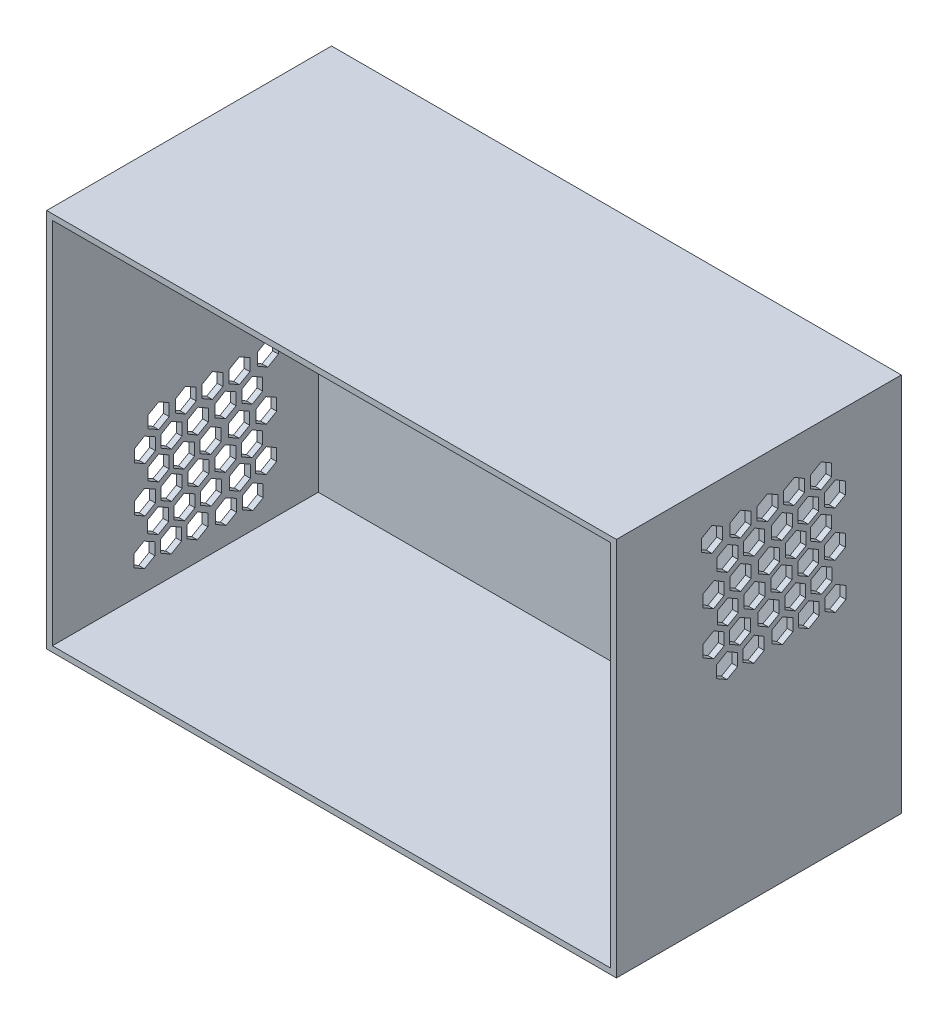
SolidWorks part; units mm, degrees
ref_plane "Plan de face" through (0, 0, 0) normal (0, 0, 1) x (1, 0, 0)
ref_plane "Plan de dessus" through (0, 0, 0) normal (0, 1, 0) x (1, 0, 0)
ref_plane "Plan de droite" through (0, 0, 0) normal (1, 0, 0) x (0, 0, -1)
sketch "Esquisse4" plane through (0, 0, 0) normal (0, 0, 1) x (1, 0, 0)
  line L1 (-89.6759, 50.5147) -> (60.3241, 50.5147)
  line L2 (-89.6759, 50.5147) -> (-89.6759, -49.4853)
  line L3 (-89.6759, -49.4853) -> (60.3241, -49.4853)
  line L4 (60.3241, 50.5147) -> (60.3241, -49.4853)
  dimension "D1" = 150
  dimension "D2" = 100
extrude "Boss.-Extru.7" add sketch "Esquisse4" along normal blind 75
sketch "Esquisse9" plane through (0, 0, 75) normal (0, 0, 1) x (1, 0, 0)
  line L0 (-89.6759, 50.5147) -> (-89.6759, -49.4853) construction
  line L1 (-88.1759, 49.0147) -> (58.8241, 49.0147)
  line L2 (-88.1759, 49.0147) -> (-88.1759, -47.9853)
  line L3 (-88.1759, -47.9853) -> (58.8241, -47.9853)
  line L4 (58.8241, 49.0147) -> (58.8241, -47.9853)
  line L5 (-89.6759, -49.4853) -> (60.3241, -49.4853) construction
  dimension "D1" = 147
  dimension "D2" = 97
  dimension "D3" = 1.5
  dimension "D4" = 1.5
extrude "Enlèv. mat.-Extru.3" cut sketch "Esquisse9" against normal blind 70
sketch "Esquisse10" plane through (60.3241, 0, 0) normal (1, 0, 0) x (0, 0, -1)
  line L0 (-38.5498, 22.7048) -> (-41.4392, 21.1145)
  line L1 (-45.6936, 22.5237) -> (-48.448, 20.9334)
  line L2 (-48.448, 20.9334) -> (-48.448, 17.7529)
  line L3 (-48.448, 17.7529) -> (-45.6936, 16.1627)
  line L4 (-45.6936, 16.1627) -> (-42.9392, 17.7529)
  line L5 (-42.9392, 17.7529) -> (-42.9392, 20.9334)
  line L6 (-42.9392, 20.9334) -> (-45.6936, 22.5237)
  line L7 (-41.4392, 21.1145) -> (-41.4392, 17.9341)
  line L8 (-41.4392, 17.9341) -> (-38.6849, 16.3438)
  line L9 (-38.6849, 16.3438) -> (-35.9305, 17.9341)
  line L10 (-35.9305, 17.9341) -> (-35.9305, 21.1145)
  line L11 (-35.9305, 21.1145) -> (-38.5498, 22.7048)
  line L12 (-42.3123, 28.6645) -> (-45.0667, 27.0742)
  line L13 (-45.0667, 27.0742) -> (-45.0667, 23.8938)
  line L14 (-45.0667, 23.8938) -> (-42.3123, 22.3035)
  line L15 (-42.3123, 22.3035) -> (-39.558, 23.8938)
  line L16 (-39.558, 23.8938) -> (-39.558, 27.0742)
  line L17 (-39.558, 27.0742) -> (-42.3123, 28.6645)
  line L18 (-27.6565, 28.8896) -> (-30.5459, 27.2993)
  line L19 (-34.8003, 28.7084) -> (-37.5547, 27.1182)
  line L20 (-37.5547, 27.1182) -> (-37.5547, 23.9377)
  line L21 (-37.5547, 23.9377) -> (-34.8003, 22.3475)
  line L22 (-34.8003, 22.3475) -> (-32.0459, 23.9377)
  line L23 (-32.0459, 23.9377) -> (-32.0459, 27.1182)
  line L24 (-32.0459, 27.1182) -> (-34.8003, 28.7084)
  line L25 (-30.5459, 27.2993) -> (-30.5459, 24.1188)
  line L26 (-30.5459, 24.1188) -> (-27.7915, 22.5286)
  line L27 (-27.7915, 22.5286) -> (-25.0372, 24.1188)
  line L28 (-25.0372, 24.1188) -> (-25.0372, 27.2993)
  line L29 (-25.0372, 27.2993) -> (-27.6565, 28.8896)
  line L30 (-31.419, 34.8493) -> (-34.1734, 33.259)
  line L31 (-34.1734, 33.259) -> (-34.1734, 30.0785)
  line L32 (-34.1734, 30.0785) -> (-31.419, 28.4883)
  line L33 (-31.419, 28.4883) -> (-28.6646, 30.0785)
  line L34 (-28.6646, 30.0785) -> (-28.6646, 33.259)
  line L35 (-28.6646, 33.259) -> (-31.419, 34.8493)
  line L36 (-27.7837, 17.0435) -> (-30.6731, 15.4533)
  line L37 (-34.9275, 16.8624) -> (-37.6819, 15.2722)
  line L38 (-37.6819, 15.2722) -> (-37.6819, 12.0917)
  line L39 (-37.6819, 12.0917) -> (-34.9275, 10.5014)
  line L40 (-34.9275, 10.5014) -> (-32.1731, 12.0917)
  line L41 (-32.1731, 12.0917) -> (-32.1731, 15.2722)
  line L42 (-32.1731, 15.2722) -> (-34.9275, 16.8624)
  line L43 (-30.6731, 15.4533) -> (-30.6731, 12.2728)
  line L44 (-30.6731, 12.2728) -> (-27.9188, 10.6826)
  line L45 (-27.9188, 10.6826) -> (-25.1644, 12.2728)
  line L46 (-25.1644, 12.2728) -> (-25.1644, 15.4533)
  line L47 (-25.1644, 15.4533) -> (-27.7837, 17.0435)
  line L48 (-31.5462, 23.0032) -> (-34.3006, 21.413)
  line L49 (-34.3006, 21.413) -> (-34.3006, 18.2325)
  line L50 (-34.3006, 18.2325) -> (-31.5462, 16.6423)
  line L51 (-31.5462, 16.6423) -> (-28.7919, 18.2325)
  line L52 (-28.7919, 18.2325) -> (-28.7919, 21.413)
  line L53 (-28.7919, 21.413) -> (-31.5462, 23.0032)
  line L54 (-38.7246, 10.5407) -> (-41.614, 8.9505)
  line L55 (-45.8684, 10.3596) -> (-48.6227, 8.7693)
  line L56 (-48.6227, 8.7693) -> (-48.6227, 5.5889)
  line L57 (-48.6227, 5.5889) -> (-45.8684, 3.9986)
  line L58 (-45.8684, 3.9986) -> (-43.114, 5.5889)
  line L59 (-43.114, 5.5889) -> (-43.114, 8.7693)
  line L60 (-43.114, 8.7693) -> (-45.8684, 10.3596)
  line L61 (-41.614, 8.9505) -> (-41.614, 5.77)
  line L62 (-41.614, 5.77) -> (-38.8596, 4.1797)
  line L63 (-38.8596, 4.1797) -> (-36.1052, 5.77)
  line L64 (-36.1052, 5.77) -> (-36.1052, 8.9505)
  line L65 (-36.1052, 8.9505) -> (-38.7246, 10.5407)
  line L66 (-42.4871, 16.5004) -> (-45.2415, 14.9102)
  line L67 (-45.2415, 14.9102) -> (-45.2415, 11.7297)
  line L68 (-45.2415, 11.7297) -> (-42.4871, 10.1394)
  line L69 (-42.4871, 10.1394) -> (-39.7327, 11.7297)
  line L70 (-39.7327, 11.7297) -> (-39.7327, 14.9102)
  line L71 (-39.7327, 14.9102) -> (-42.4871, 16.5004)
  line L84 (-31.2918, 11.0153) -> (-34.0462, 9.4251)
  line L85 (-34.0462, 9.4251) -> (-34.0462, 6.2446)
  line L86 (-34.0462, 6.2446) -> (-31.2918, 4.6544)
  line L87 (-31.2918, 4.6544) -> (-28.5374, 6.2446)
  line L88 (-28.5374, 6.2446) -> (-28.5374, 9.4251)
  line L89 (-28.5374, 9.4251) -> (-31.2918, 11.0153)
  line L90 (-17.2245, 11.4019) -> (-20.1139, 9.8117)
  line L91 (-24.3683, 11.2208) -> (-27.1227, 9.6306)
  line L92 (-27.1227, 9.6306) -> (-27.1227, 6.4501)
  line L93 (-27.1227, 6.4501) -> (-24.3683, 4.8599)
  line L94 (-24.3683, 4.8599) -> (-21.6139, 6.4501)
  line L95 (-21.6139, 6.4501) -> (-21.6139, 9.6306)
  line L96 (-21.6139, 9.6306) -> (-24.3683, 11.2208)
  line L97 (-20.1139, 9.8117) -> (-20.1139, 6.6312)
  line L98 (-20.1139, 6.6312) -> (-17.3596, 5.041)
  line L99 (-17.3596, 5.041) -> (-14.6052, 6.6312)
  line L100 (-14.6052, 6.6312) -> (-14.6052, 9.8117)
  line L101 (-14.6052, 9.8117) -> (-17.2245, 11.4019)
  line L102 (-20.987, 17.3616) -> (-23.7414, 15.7714)
  line L103 (-23.7414, 15.7714) -> (-23.7414, 12.5909)
  line L104 (-23.7414, 12.5909) -> (-20.987, 11.0007)
  line L105 (-20.987, 11.0007) -> (-18.2327, 12.5909)
  line L106 (-18.2327, 12.5909) -> (-18.2327, 15.7714)
  line L107 (-18.2327, 15.7714) -> (-20.987, 17.3616)
  line L108 (-17.3518, 23.3459) -> (-20.2412, 21.7556)
  line L109 (-24.4955, 23.1648) -> (-27.2499, 21.5745)
  line L110 (-27.2499, 21.5745) -> (-27.2499, 18.394)
  line L111 (-27.2499, 18.394) -> (-24.4955, 16.8038)
  line L112 (-24.4955, 16.8038) -> (-21.7412, 18.394)
  line L113 (-21.7412, 18.394) -> (-21.7412, 21.5745)
  line L114 (-21.7412, 21.5745) -> (-24.4955, 23.1648)
  line L115 (-20.2412, 21.7556) -> (-20.2412, 18.5752)
  line L116 (-20.2412, 18.5752) -> (-17.4868, 16.9849)
  line L117 (-17.4868, 16.9849) -> (-14.7324, 18.5752)
  line L118 (-14.7324, 18.5752) -> (-14.7324, 21.7556)
  line L119 (-14.7324, 21.7556) -> (-17.3518, 23.3459)
  line L120 (-21.1143, 29.3056) -> (-23.8686, 27.7154)
  line L121 (-23.8686, 27.7154) -> (-23.8686, 24.5349)
  line L122 (-23.8686, 24.5349) -> (-21.1143, 22.9446)
  line L123 (-21.1143, 22.9446) -> (-18.3599, 24.5349)
  line L124 (-18.3599, 24.5349) -> (-18.3599, 27.7154)
  line L125 (-18.3599, 27.7154) -> (-21.1143, 29.3056)
  line L126 (-38.5974, 34.9082) -> (-41.4868, 33.3179)
  line L127 (-45.7411, 34.7271) -> (-48.4955, 33.1368)
  line L128 (-48.4955, 33.1368) -> (-48.4955, 29.9563)
  line L129 (-48.4955, 29.9563) -> (-45.7411, 28.3661)
  line L130 (-45.7411, 28.3661) -> (-42.9868, 29.9563)
  line L131 (-42.9868, 29.9563) -> (-42.9868, 33.1368)
  line L132 (-42.9868, 33.1368) -> (-45.7411, 34.7271)
  line L133 (-41.4868, 33.3179) -> (-41.4868, 30.1375)
  line L134 (-41.4868, 30.1375) -> (-38.7324, 28.5472)
  line L135 (-38.7324, 28.5472) -> (-35.978, 30.1375)
  line L136 (-35.978, 30.1375) -> (-35.978, 33.3179)
  line L137 (-35.978, 33.3179) -> (-38.5974, 34.9082)
  line L138 (-42.3599, 40.8679) -> (-45.1142, 39.2776)
  line L139 (-45.1142, 39.2776) -> (-45.1142, 36.0972)
  line L140 (-45.1142, 36.0972) -> (-42.3599, 34.5069)
  line L141 (-42.3599, 34.5069) -> (-39.6055, 36.0972)
  line L142 (-39.6055, 36.0972) -> (-39.6055, 39.2776)
  line L143 (-39.6055, 39.2776) -> (-42.3599, 40.8679)
  line L144 (-17.3518, 35.2752) -> (-20.2412, 33.6849)
  line L145 (-24.4955, 35.0941) -> (-27.2499, 33.5038)
  line L146 (-27.2499, 33.5038) -> (-27.2499, 30.3233)
  line L147 (-27.2499, 30.3233) -> (-24.4955, 28.7331)
  line L148 (-24.4955, 28.7331) -> (-21.7412, 30.3233)
  line L149 (-21.7412, 30.3233) -> (-21.7412, 33.5038)
  line L150 (-21.7412, 33.5038) -> (-24.4955, 35.0941)
  line L151 (-20.2412, 33.6849) -> (-20.2412, 30.5045)
  line L152 (-20.2412, 30.5045) -> (-17.4868, 28.9142)
  line L153 (-17.4868, 28.9142) -> (-14.7324, 30.5045)
  line L154 (-14.7324, 30.5045) -> (-14.7324, 33.6849)
  line L155 (-14.7324, 33.6849) -> (-17.3518, 35.2752)
  line L156 (-21.1143, 41.2349) -> (-23.8686, 39.6447)
  line L157 (-23.8686, 39.6447) -> (-23.8686, 36.4642)
  line L158 (-23.8686, 36.4642) -> (-21.1143, 34.8739)
  line L159 (-21.1143, 34.8739) -> (-18.3599, 36.4642)
  line L160 (-18.3599, 36.4642) -> (-18.3599, 39.6447)
  line L161 (-18.3599, 39.6447) -> (-21.1143, 41.2349)
  line L162 (-49.3041, 28.294) -> (-52.1935, 26.7038)
  line L163 (-49.8529, 41.1198) -> (-52.6072, 39.5295)
  line L164 (-52.6072, 39.5295) -> (-52.6072, 36.3491)
  line L165 (-52.6072, 36.3491) -> (-49.8529, 34.7588)
  line L166 (-49.8529, 34.7588) -> (-47.0985, 36.3491)
  line L167 (-47.0985, 36.3491) -> (-47.0985, 39.5295)
  line L168 (-47.0985, 39.5295) -> (-49.8529, 41.1198)
  line L169 (-52.1935, 26.7038) -> (-52.1935, 23.5233)
  line L170 (-52.1935, 23.5233) -> (-49.4392, 21.9331)
  line L171 (-49.4392, 21.9331) -> (-46.6848, 23.5233)
  line L172 (-46.6848, 23.5233) -> (-46.6848, 26.7038)
  line L173 (-46.6848, 26.7038) -> (-49.3041, 28.294)
  line L174 (-49.4027, 16.8501) -> (-52.1571, 15.2599)
  line L175 (-52.1571, 15.2599) -> (-52.1571, 12.0794)
  line L176 (-52.1571, 12.0794) -> (-49.4027, 10.4892)
  line L177 (-49.4027, 10.4892) -> (-46.6483, 12.0794)
  line L178 (-46.6483, 12.0794) -> (-46.6483, 15.2599)
  line L179 (-46.6483, 15.2599) -> (-49.4027, 16.8501)
  line L180 (-28.1038, 41.2272) -> (-30.9932, 39.6369)
  line L181 (-35.2476, 41.046) -> (-38.002, 39.4558)
  line L182 (-38.002, 39.4558) -> (-38.002, 36.2753)
  line L183 (-38.002, 36.2753) -> (-35.2476, 34.6851)
  line L184 (-35.2476, 34.6851) -> (-32.4932, 36.2753)
  line L185 (-32.4932, 36.2753) -> (-32.4932, 39.4558)
  line L186 (-32.4932, 39.4558) -> (-35.2476, 41.046)
  line L187 (-30.9932, 39.6369) -> (-30.9932, 36.4564)
  line L188 (-30.9932, 36.4564) -> (-28.2389, 34.8662)
  line L189 (-28.2389, 34.8662) -> (-25.4845, 36.4564)
  line L190 (-25.4845, 36.4564) -> (-25.4845, 39.6369)
  line L191 (-25.4845, 39.6369) -> (-28.1038, 41.2272)
  circle A0 centre (-45.6936, 19.3432) radius 2.7544 construction
  point P20 (-39.9945, 21.9097)
  dimension "D1" = 1.5
  dimension "D2" = 1.5
  dimension "D3" = 1.5
extrude "Enlèv. mat.-Extru.5" cut sketch "Esquisse10" against normal blind 4
sketch "Esquisse13" plane through (-89.6759, 0, 0) normal (-1, 0, 0) x (0, 0, 1)
  line L0 (29.5778, -24.8706) -> (26.6884, -26.4609)
  line L1 (22.434, -25.0517) -> (19.6796, -26.642)
  line L2 (19.6796, -26.642) -> (19.6796, -29.8225)
  line L3 (19.6796, -29.8225) -> (22.434, -31.4127)
  line L4 (22.434, -31.4127) -> (25.1884, -29.8225)
  line L5 (25.1884, -29.8225) -> (25.1884, -26.642)
  line L6 (25.1884, -26.642) -> (22.434, -25.0517)
  line L7 (26.6884, -26.4609) -> (26.6884, -29.6413)
  line L8 (26.6884, -29.6413) -> (29.4428, -31.2316)
  line L9 (29.4428, -31.2316) -> (32.1971, -29.6413)
  line L10 (32.1971, -29.6413) -> (32.1971, -26.4609)
  line L11 (32.1971, -26.4609) -> (29.5778, -24.8706)
  line L12 (25.8153, -18.9109) -> (23.0609, -20.5012)
  line L13 (23.0609, -20.5012) -> (23.0609, -23.6816)
  line L14 (23.0609, -23.6816) -> (25.8153, -25.2719)
  line L15 (25.8153, -25.2719) -> (28.5697, -23.6816)
  line L16 (28.5697, -23.6816) -> (28.5697, -20.5012)
  line L17 (28.5697, -20.5012) -> (25.8153, -18.9109)
  line L18 (40.4711, -18.6858) -> (37.5817, -20.2761)
  line L19 (33.3273, -18.867) -> (30.573, -20.4572)
  line L20 (30.573, -20.4572) -> (30.573, -23.6377)
  line L21 (30.573, -23.6377) -> (33.3273, -25.2279)
  line L22 (33.3273, -25.2279) -> (36.0817, -23.6377)
  line L23 (36.0817, -23.6377) -> (36.0817, -20.4572)
  line L24 (36.0817, -20.4572) -> (33.3273, -18.867)
  line L25 (37.5817, -20.2761) -> (37.5817, -23.4566)
  line L26 (37.5817, -23.4566) -> (40.3361, -25.0468)
  line L27 (40.3361, -25.0468) -> (43.0905, -23.4566)
  line L28 (43.0905, -23.4566) -> (43.0905, -20.2761)
  line L29 (43.0905, -20.2761) -> (40.4711, -18.6858)
  line L30 (36.7086, -12.7261) -> (33.9542, -14.3164)
  line L31 (33.9542, -14.3164) -> (33.9542, -17.4969)
  line L32 (33.9542, -17.4969) -> (36.7086, -19.0871)
  line L33 (36.7086, -19.0871) -> (39.463, -17.4969)
  line L34 (39.463, -17.4969) -> (39.463, -14.3164)
  line L35 (39.463, -14.3164) -> (36.7086, -12.7261)
  line L36 (40.3439, -30.5319) -> (37.4545, -32.1221)
  line L37 (33.2001, -30.713) -> (30.4457, -32.3032)
  line L38 (30.4457, -32.3032) -> (30.4457, -35.4837)
  line L39 (30.4457, -35.4837) -> (33.2001, -37.074)
  line L40 (33.2001, -37.074) -> (35.9545, -35.4837)
  line L41 (35.9545, -35.4837) -> (35.9545, -32.3032)
  line L42 (35.9545, -32.3032) -> (33.2001, -30.713)
  line L43 (37.4545, -32.1221) -> (37.4545, -35.3026)
  line L44 (37.4545, -35.3026) -> (40.2089, -36.8928)
  line L45 (40.2089, -36.8928) -> (42.9632, -35.3026)
  line L46 (42.9632, -35.3026) -> (42.9632, -32.1221)
  line L47 (42.9632, -32.1221) -> (40.3439, -30.5319)
  line L48 (36.5814, -24.5722) -> (33.827, -26.1624)
  line L49 (33.827, -26.1624) -> (33.827, -29.3429)
  line L50 (33.827, -29.3429) -> (36.5814, -30.9331)
  line L51 (36.5814, -30.9331) -> (39.3358, -29.3429)
  line L52 (39.3358, -29.3429) -> (39.3358, -26.1624)
  line L53 (39.3358, -26.1624) -> (36.5814, -24.5722)
  line L54 (29.403, -37.0347) -> (26.5136, -38.6249)
  line L55 (22.2593, -37.2158) -> (19.5049, -38.8061)
  line L56 (19.5049, -38.8061) -> (19.5049, -41.9865)
  line L57 (19.5049, -41.9865) -> (22.2593, -43.5768)
  line L58 (22.2593, -43.5768) -> (25.0136, -41.9865)
  line L59 (25.0136, -41.9865) -> (25.0136, -38.8061)
  line L60 (25.0136, -38.8061) -> (22.2593, -37.2158)
  line L61 (26.5136, -38.6249) -> (26.5136, -41.8054)
  line L62 (26.5136, -41.8054) -> (29.268, -43.3957)
  line L63 (29.268, -43.3957) -> (32.0224, -41.8054)
  line L64 (32.0224, -41.8054) -> (32.0224, -38.6249)
  line L65 (32.0224, -38.6249) -> (29.403, -37.0347)
  line L66 (25.6405, -31.075) -> (22.8862, -32.6652)
  line L67 (22.8862, -32.6652) -> (22.8862, -35.8457)
  line L68 (22.8862, -35.8457) -> (25.6405, -37.436)
  line L69 (25.6405, -37.436) -> (28.3949, -35.8457)
  line L70 (28.3949, -35.8457) -> (28.3949, -32.6652)
  line L71 (28.3949, -32.6652) -> (25.6405, -31.075)
  line L84 (36.8358, -36.5601) -> (34.0815, -38.1503)
  line L85 (34.0815, -38.1503) -> (34.0815, -41.3308)
  line L86 (34.0815, -41.3308) -> (36.8358, -42.921)
  line L87 (36.8358, -42.921) -> (39.5902, -41.3308)
  line L88 (39.5902, -41.3308) -> (39.5902, -38.1503)
  line L89 (39.5902, -38.1503) -> (36.8358, -36.5601)
  line L90 (50.9031, -36.1735) -> (48.0137, -37.7637)
  line L91 (43.7593, -36.3546) -> (41.0049, -37.9448)
  line L92 (41.0049, -37.9448) -> (41.0049, -41.1253)
  line L93 (41.0049, -41.1253) -> (43.7593, -42.7156)
  line L94 (43.7593, -42.7156) -> (46.5137, -41.1253)
  line L95 (46.5137, -41.1253) -> (46.5137, -37.9448)
  line L96 (46.5137, -37.9448) -> (43.7593, -36.3546)
  line L97 (48.0137, -37.7637) -> (48.0137, -40.9442)
  line L98 (48.0137, -40.9442) -> (50.7681, -42.5344)
  line L99 (50.7681, -42.5344) -> (53.5224, -40.9442)
  line L100 (53.5224, -40.9442) -> (53.5224, -37.7637)
  line L101 (53.5224, -37.7637) -> (50.9031, -36.1735)
  line L102 (47.1406, -30.2138) -> (44.3862, -31.804)
  line L103 (44.3862, -31.804) -> (44.3862, -34.9845)
  line L104 (44.3862, -34.9845) -> (47.1406, -36.5747)
  line L105 (47.1406, -36.5747) -> (49.895, -34.9845)
  line L106 (49.895, -34.9845) -> (49.895, -31.804)
  line L107 (49.895, -31.804) -> (47.1406, -30.2138)
  line L108 (50.7759, -24.2295) -> (47.8865, -25.8198)
  line L109 (43.6321, -24.4106) -> (40.8777, -26.0009)
  line L110 (40.8777, -26.0009) -> (40.8777, -29.1814)
  line L111 (40.8777, -29.1814) -> (43.6321, -30.7716)
  line L112 (43.6321, -30.7716) -> (46.3865, -29.1814)
  line L113 (46.3865, -29.1814) -> (46.3865, -26.0009)
  line L114 (46.3865, -26.0009) -> (43.6321, -24.4106)
  line L115 (47.8865, -25.8198) -> (47.8865, -29.0002)
  line L116 (47.8865, -29.0002) -> (50.6408, -30.5905)
  line L117 (50.6408, -30.5905) -> (53.3952, -29.0002)
  line L118 (53.3952, -29.0002) -> (53.3952, -25.8198)
  line L119 (53.3952, -25.8198) -> (50.7759, -24.2295)
  line L120 (47.0134, -18.2698) -> (44.259, -19.8601)
  line L121 (44.259, -19.8601) -> (44.259, -23.0405)
  line L122 (44.259, -23.0405) -> (47.0134, -24.6308)
  line L123 (47.0134, -24.6308) -> (49.7677, -23.0405)
  line L124 (49.7677, -23.0405) -> (49.7677, -19.8601)
  line L125 (49.7677, -19.8601) -> (47.0134, -18.2698)
  line L126 (29.5303, -12.6672) -> (26.6409, -14.2575)
  line L127 (22.3865, -12.8483) -> (19.6321, -14.4386)
  line L128 (19.6321, -14.4386) -> (19.6321, -17.6191)
  line L129 (19.6321, -17.6191) -> (22.3865, -19.2093)
  line L130 (22.3865, -19.2093) -> (25.1409, -17.6191)
  line L131 (25.1409, -17.6191) -> (25.1409, -14.4386)
  line L132 (25.1409, -14.4386) -> (22.3865, -12.8483)
  line L133 (26.6409, -14.2575) -> (26.6409, -17.4379)
  line L134 (26.6409, -17.4379) -> (29.3952, -19.0282)
  line L135 (29.3952, -19.0282) -> (32.1496, -17.4379)
  line L136 (32.1496, -17.4379) -> (32.1496, -14.2575)
  line L137 (32.1496, -14.2575) -> (29.5303, -12.6672)
  line L138 (25.7678, -6.7075) -> (23.0134, -8.2978)
  line L139 (23.0134, -8.2978) -> (23.0134, -11.4782)
  line L140 (23.0134, -11.4782) -> (25.7678, -13.0685)
  line L141 (25.7678, -13.0685) -> (28.5221, -11.4782)
  line L142 (28.5221, -11.4782) -> (28.5221, -8.2978)
  line L143 (28.5221, -8.2978) -> (25.7678, -6.7075)
  line L144 (50.7759, -12.3002) -> (47.8865, -13.8905)
  line L145 (43.6321, -12.4813) -> (40.8777, -14.0716)
  line L146 (40.8777, -14.0716) -> (40.8777, -17.2521)
  line L147 (40.8777, -17.2521) -> (43.6321, -18.8423)
  line L148 (43.6321, -18.8423) -> (46.3865, -17.2521)
  line L149 (46.3865, -17.2521) -> (46.3865, -14.0716)
  line L150 (46.3865, -14.0716) -> (43.6321, -12.4813)
  line L151 (47.8865, -13.8905) -> (47.8865, -17.0709)
  line L152 (47.8865, -17.0709) -> (50.6408, -18.6612)
  line L153 (50.6408, -18.6612) -> (53.3952, -17.0709)
  line L154 (53.3952, -17.0709) -> (53.3952, -13.8905)
  line L155 (53.3952, -13.8905) -> (50.7759, -12.3002)
  line L156 (47.0134, -6.3405) -> (44.259, -7.9308)
  line L157 (44.259, -7.9308) -> (44.259, -11.1112)
  line L158 (44.259, -11.1112) -> (47.0134, -12.7015)
  line L159 (47.0134, -12.7015) -> (49.7677, -11.1112)
  line L160 (49.7677, -11.1112) -> (49.7677, -7.9308)
  line L161 (49.7677, -7.9308) -> (47.0134, -6.3405)
  line L162 (18.8235, -19.2814) -> (15.9341, -20.8716)
  line L163 (18.2748, -6.4556) -> (15.5204, -8.0459)
  line L164 (15.5204, -8.0459) -> (15.5204, -11.2263)
  line L165 (15.5204, -11.2263) -> (18.2748, -12.8166)
  line L166 (18.2748, -12.8166) -> (21.0291, -11.2263)
  line L167 (21.0291, -11.2263) -> (21.0291, -8.0459)
  line L168 (21.0291, -8.0459) -> (18.2748, -6.4556)
  line L169 (15.9341, -20.8716) -> (15.9341, -24.0521)
  line L170 (15.9341, -24.0521) -> (18.6885, -25.6423)
  line L171 (18.6885, -25.6423) -> (21.4428, -24.0521)
  line L172 (21.4428, -24.0521) -> (21.4428, -20.8716)
  line L173 (21.4428, -20.8716) -> (18.8235, -19.2814)
  line L174 (18.7249, -30.7253) -> (15.9705, -32.3155)
  line L175 (15.9705, -32.3155) -> (15.9705, -35.496)
  line L176 (15.9705, -35.496) -> (18.7249, -37.0862)
  line L177 (18.7249, -37.0862) -> (21.4793, -35.496)
  line L178 (21.4793, -35.496) -> (21.4793, -32.3155)
  line L179 (21.4793, -32.3155) -> (18.7249, -30.7253)
  line L180 (40.0238, -6.3483) -> (37.1344, -7.9385)
  line L181 (32.88, -6.5294) -> (30.1256, -8.1196)
  line L182 (30.1256, -8.1196) -> (30.1256, -11.3001)
  line L183 (30.1256, -11.3001) -> (32.88, -12.8903)
  line L184 (32.88, -12.8903) -> (35.6344, -11.3001)
  line L185 (35.6344, -11.3001) -> (35.6344, -8.1196)
  line L186 (35.6344, -8.1196) -> (32.88, -6.5294)
  line L187 (37.1344, -7.9385) -> (37.1344, -11.119)
  line L188 (37.1344, -11.119) -> (39.8888, -12.7092)
  line L189 (39.8888, -12.7092) -> (42.6431, -11.119)
  line L190 (42.6431, -11.119) -> (42.6431, -7.9385)
  line L191 (42.6431, -7.9385) -> (40.0238, -6.3483)
  circle A0 centre (22.434, -28.2322) radius 2.7544 construction
  point P20 (28.1331, -25.6657)
  dimension "D1" = 1.5
  dimension "D2" = 1.5
  dimension "D3" = 1.5
extrude "Enlèv. mat.-Extru.8" cut sketch "Esquisse13" against normal blind 4
